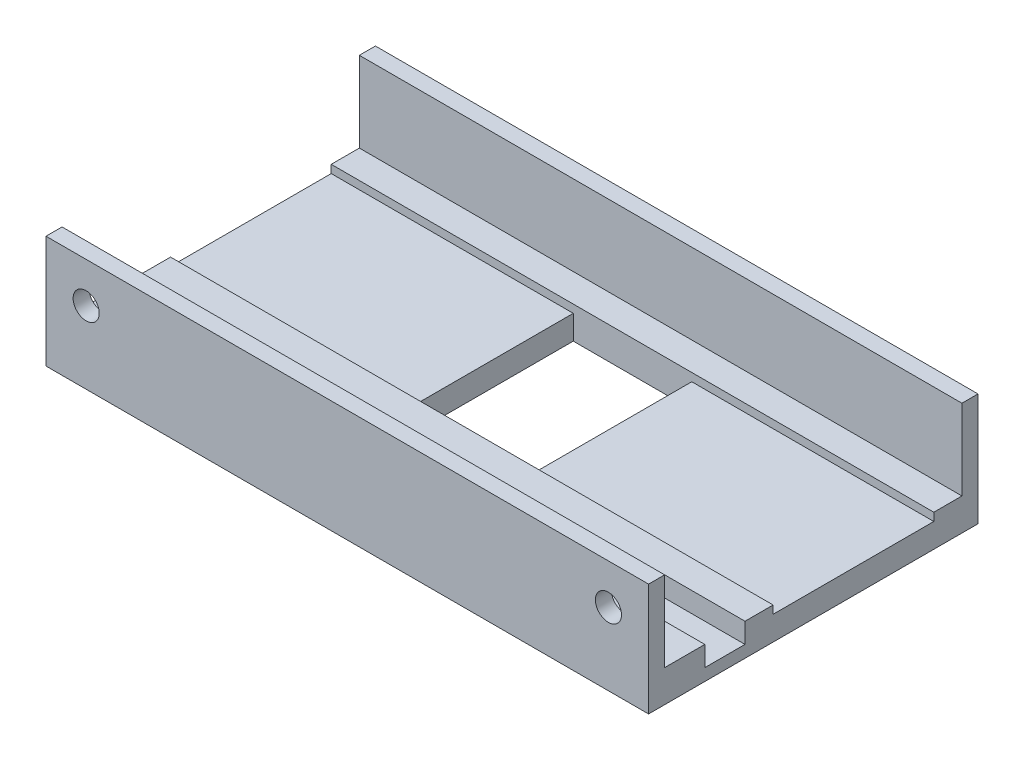
SolidWorks part; units mm, degrees
material "1345 Alloy"
ref_plane "Front Plane" through (0, 0, 0) normal (0, 0, 1) x (1, 0, 0)
ref_plane "Top Plane" through (0, 0, 0) normal (0, 1, 0) x (1, 0, 0)
ref_plane "Right Plane" through (0, 0, 0) normal (1, 0, 0) x (0, 0, -1)
sketch "Sketch1" plane through (0, 0, 0) normal (0, 1, 0) x (1, 0, 0)
  line L1 (-37.5, 20.5) -> (37.5, 20.5)
  line L2 (-37.5, 20.5) -> (-37.5, -20.5)
  line L3 (-37.5, -20.5) -> (37.5, -20.5)
  line L4 (37.5, 20.5) -> (37.5, -20.5)
  line L5 (-37.5, 20.5) -> (37.5, -20.5) construction
  line L6 (-37.5, -20.5) -> (37.5, 20.5) construction
  point P0 (0, 0)
  dimension "D1" = 41
  dimension "D2" = 75
extrude "Boss-Extrude1" add sketch "Sketch1" along normal blind 4
sketch "Sketch2" plane through (0, 4, 0) normal (0, 1, 0) x (1, 0, 0)
  line L0 (37.5, -20.5) -> (37.5, 20.5) construction
  line L1 (-37.5, 20.5) -> (37.5, 20.5)
  line L2 (-37.5, 20.5) -> (-37.5, 18.5)
  line L3 (-37.5, 18.5) -> (37.5, 18.5)
  line L4 (37.5, 20.5) -> (37.5, 18.5)
  dimension "D1" = 2
extrude "Boss-Extrude2" add sketch "Sketch2" along normal blind 10
sketch "Sketch3" plane through (0, 4, 0) normal (0, 1, 0) x (1, 0, 0)
  line L0 (37.5, -20.5) -> (37.5, 18.5) construction
  line L1 (-37.5, -20.5) -> (37.5, -20.5)
  line L2 (-37.5, -20.5) -> (-37.5, -18.5)
  line L3 (-37.5, -18.5) -> (37.5, -18.5)
  line L4 (37.5, -20.5) -> (37.5, -18.5)
  dimension "D1" = 2
extrude "Boss-Extrude3" add sketch "Sketch3" along normal up to surface (10 mm away) up to face at (0, 14, -19.5)
sketch "Sketch6" plane through (0, 4, 0) normal (0, 1, 0) x (1, 0, 0)
  line L0 (-37.5, 18.5) -> (-37.5, -9.5) construction
  line L2 (-37.5, -9.5) -> (37.5039, -9.5) construction
  line L4 (37.5039, -9.5) -> (37.5, 18.5) construction
  line L5 (37.5, 18.5) -> (-37.5, 18.5) construction
  line L7 (-37.5, 5) -> (37.5, 5) construction
  line L8 (0, 18.5) -> (0, -8.5) construction
  line L10 (-7.375, 15) -> (7.375, 15)
  line L11 (-7.375, 15) -> (-7.375, -5)
  line L12 (-7.375, -5) -> (7.375, -5)
  line L13 (7.375, 15) -> (7.375, -5)
  line L14 (-7.375, 15) -> (7.375, -5) construction
  line L15 (-7.375, -5) -> (7.375, 15) construction
  line L16 (-37.5, 18.5) -> (-37.5, -18.5) construction
  line L17 (-22.8126, -9.5) -> (22.1874, -9.5) construction
  point P17 (0, 5)
  dimension "D1" = 14.75
  dimension "D2" = 20
  dimension "D3" = 4.5
extrude "Cut-Extrude3" cut sketch "Sketch6" against normal through all
sketch "Sketch7" plane through (0, 4, 0) normal (0, 1, 0) x (1, 0, 0)
  line L0 (-37.5, 18.5) -> (-37.5, -18.5) construction
  line L1 (-37.5, 15) -> (37.5, 15)
  line L2 (-37.5, 15) -> (-37.5, -5)
  line L3 (-37.5, -5) -> (37.5, -5)
  line L4 (37.5, 15) -> (37.5, -5)
  line L5 (37.5, -18.5) -> (37.5, 18.5) construction
  line L6 (7.375, 15) -> (-7.375, 15) construction
  line L7 (-7.375, -5) -> (7.375, -5) construction
extrude "Cut-Extrude4" cut sketch "Sketch7" against normal blind 1
sketch "Sketch10" plane through (0, 0, 20.5) normal (0, 0, 1) x (1, 0, 0)
  line L0 (0, 0) -> (0, 14) construction
  line L1 (-37.5, 0) -> (37.5, 0) construction
  line L2 (-37.5, 14) -> (37.5, 14) construction
  circle A0 centre (-32.5, 9) radius 1.625
  circle A1 centre (32.5, 9) radius 1.625
  dimension "D1" = 3.25
extrude "Cut-Extrude5" cut sketch "Sketch10" against normal up to surface (2 mm away) up to face at (0, 9, 18.5)
sketch "Sketch11" plane through (0, 4, 0) normal (0, 1, 0) x (1, 0, 0)
  line L0 (0, 0) -> (0, -20.5) construction
  line L1 (-37.5, -8.5) -> (-37.5, -13.5)
  line L2 (-37.5, -20.5) -> (37.5, -20.5) construction
  line L5 (-37.5, -5) -> (-37.5, -18.5) construction
  line L6 (-37.5, -13.5) -> (-27, -13.5)
  line L7 (-27, -13.5) -> (-27, -8.5)
  line L8 (-27, -8.5) -> (-37.5, -8.5)
  line L12 (27, -8.5) -> (37.5, -8.5)
  line L13 (27, -13.5) -> (27, -8.5)
  line L14 (37.5, -13.5) -> (27, -13.5)
  line L15 (37.5, -8.5) -> (37.5, -13.5)
  line L17 (-27.5, -9.5) -> (-27.5, -11.5) construction
  line L18 (37.5, -18.5) -> (-37.5, -18.5) construction
  line L21 (-28.6857, -8.5) -> (-37.5, -8.5) construction
  dimension "D1" = 0.5
  dimension "D2" = 5
extrude "Cut-Extrude6" cut sketch "Sketch11" against normal blind 2.5
